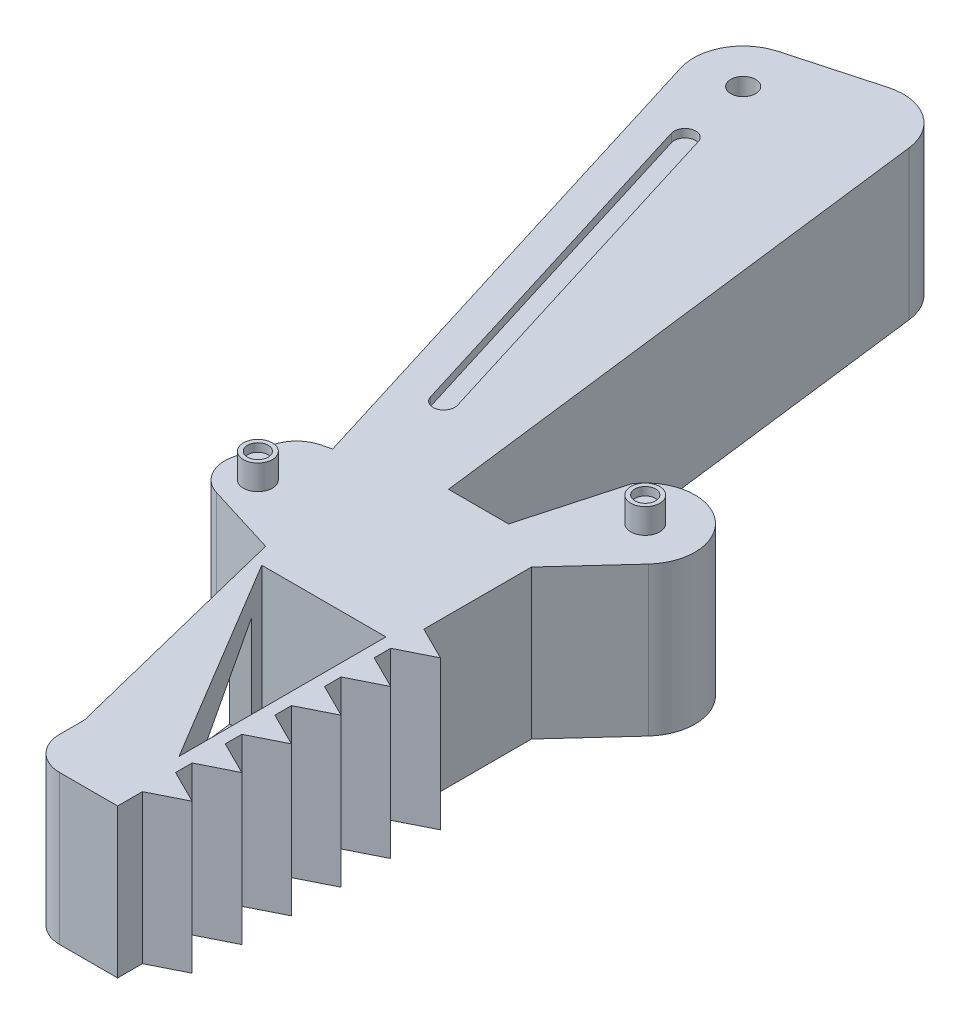
SolidWorks part; units mm, degrees
ref_plane "Plan de face" through (0, 0, 0) normal (0, 0, 1) x (1, 0, 0)
ref_plane "Plan de dessus" through (0, 0, 0) normal (0, 1, 0) x (1, 0, 0)
ref_plane "Plan de droite" through (0, 0, 0) normal (1, 0, 0) x (0, 0, -1)
sketch "Esquisse1" plane through (0, 0, 0) normal (0, 1, 0) x (1, 0, 0)
  line L0 (0, 0) -> (-69.0933, 0) construction
  line L1 (-15.9314, 0) -> (-39.0702, -6.3713)
  line L2 (-39.0702, -6.3713) -> (-18.3784, -73.2431)
  line L3 (-15.9314, 0) -> (-7.1627, -70.4564)
  line L4 (-7.1627, -70.4564) -> (-21.7201, -74.0734)
  line L5 (-21.7201, -74.0734) -> (-24.6742, -83.6271)
  line L6 (-24.6742, -83.6271) -> (-12.2544, -87.4675)
  line L7 (-12.2544, -87.4675) -> (-5.0204, -116.5822)
  line L8 (-5.0204, -116.5822) -> (-5.0204, -123.5822)
  line L9 (-5.0204, -123.5822) -> (5.9796, -123.5822)
  line L10 (5.9796, -123.5822) -> (5.9796, -73.5822)
  line L11 (5.9796, -73.5822) -> (12.7296, -66.2041)
  line L12 (-7.1627, -70.4564) -> (0.0908, -70.4564)
  line L13 (0.0908, -70.4564) -> (3.3228, -58.8074)
  arc A0 (3.3228, -58.8074) -> (12.7296, -66.2041) centre (8.3027, -62.1541) cw
  dimension "D12" = 6
  dimension "D1" = 24
  dimension "D2" = 70
  dimension "D3" = 71
  dimension "D4" = 15
  dimension "D5" = 10
  dimension "D6" = 13
  dimension "D7" = 30
  dimension "D8" = 7
  dimension "D9" = 11
  dimension "D10" = 50
  dimension "D11" = 10
extrude "Boss.-Extru.1" add sketch "Esquisse1" along normal mid plane 18
fillet "Congé1" radius 6 2 edges at (-15.9314, 0, 0) (-39.0702, 0, 6.3713)
fillet "Congé2" radius 4 3 edges at (-5.0204, 0, 123.5822) (-24.6742, 0, 83.6271) (-21.7201, 0, 74.0734)
sketch "Esquisse2" plane through (0, 9, 0) normal (0, 1, 0) x (1, 0, 0)
  line L0 (5.9796, -123.5822) -> (5.9796, -118.5822)
  line L1 (5.9796, -123.5822) -> (5.9796, -73.5822) construction
  line L2 (5.9796, -118.5822) -> (9.9796, -118.5822) construction
  line L3 (5.9796, -116.5822) -> (5.9796, -120.5822)
  line L4 (5.9796, -116.5822) -> (9.9796, -118.5822)
  line L5 (9.9796, -118.5822) -> (5.9796, -120.5822)
  point P9 (5.9796, -118.5822)
  line M7 (5.9796, -123.5822) -> (5.9796, -73.5822)
  dimension "D1" = 5
  dimension "D2" = 4
  dimension "D3" = 4
extrude "Boss.-Extru.2" add sketch "Esquisse2" against normal through all contours L2 L4 M7 | L2 L0 L5
pattern_linear "Répétition linéaire1" count 6 spacing 6 along (0, 0, -1) of "Boss.-Extru.2"
sketch "Esquisse3" plane through (0, 9, 0) normal (0, 1, 0) x (1, 0, 0)
  line L0 (4.5005, -114.6826) -> (4.5005, -89.6826)
  line L1 (4.5005, -89.6826) -> (-10.4995, -89.6826)
  line L2 (-10.4995, -89.6826) -> (4.5005, -114.6826)
  dimension "D1" = 15
  dimension "D2" = 25
extrude "Enlèv. mat.-Extru.1" cut sketch "Esquisse3" against normal through all
sketch "Esquisse4" plane through (-32.0108, 0, 7.9536) normal (-0.9705, 0, 0.2411) x (0.2411, 0, 0.9705)
  line L0 (87.9316, 6) -> (87.9316, -6)
  line L1 (87.9316, -6) -> (105.9316, -3.5)
  line L2 (105.9316, -3.5) -> (105.9316, 3.5)
  line L3 (105.9316, 3.5) -> (87.9316, 6)
  line L4 (81.9316, 9) -> (81.9316, -9) construction
  line L6 (111.9316, 9) -> (111.9316, -9) construction
  line L7 (81.9316, 9) -> (111.9316, 9) construction
  point P4 (87.9316, 0)
  point P5 (105.9316, 0)
  point P8 (81.9316, 0)
  dimension "D1" = 3
  dimension "D2" = 6
  dimension "D3" = 6
extrude "Enlèv. mat.-Extru.2" cut sketch "Esquisse4" against normal blind 10
sketch "Esquisse5" plane through (0, 9, 0) normal (0, 1, 0) x (1, 0, 0)
  circle A0 centre (-31.5082, -10.5124) radius 1.5
  dimension "D1" = 3
extrude "Enlèv. mat.-Extru.3" cut sketch "Esquisse5" against normal through all
sketch "Esquisse7" plane through (0, 9, 0) normal (0, 1, 0) x (1, 0, 0)
  circle A0 centre (-19.6711, -80.9873) radius 1.75
  circle A1 centre (8.3027, -62.1541) radius 1.75
  dimension "D1" = 3.5
  dimension "D2" = 3.5
extrude "Boss.-Extru.3" add sketch "Esquisse7" along normal blind 3
sketch "Esquisse8" plane through (0, 12, 0) normal (0, 1, 0) x (1, 0, 0)
  circle A2 centre (-19.6711, -80.9873) radius 1.25
  circle A3 centre (-19.6711, -80.9873) radius 1.25
  dimension "D1" = 0.5
extrude "Enlèv. mat.-Extru.4" cut sketch "Esquisse8" against normal blind 1
sketch "Esquisse9" plane through (0, 12, 0) normal (0, 1, 0) x (1, 0, 0)
  circle A2 centre (8.3027, -62.1541) radius 1.25
  circle A3 centre (8.3027, -62.1541) radius 1.25
  dimension "D1" = 0.5
extrude "Enlèv. mat.-Extru.5" cut sketch "Esquisse9" against normal blind 1
sketch "Esquisse10" plane through (0, 9, 0) normal (0, 1, 0) x (1, 0, 0)
  line L0 (-29.7189, -19.3379) -> (-16.6676, -61.5169) construction
  line L1 (-28.4702, -18.9515) -> (-15.4189, -61.1305)
  line L2 (-30.9675, -19.7242) -> (-17.9163, -61.9032)
  line L4 (-37.2401, -12.286) -> (-18.3784, -73.2431) construction
  arc A0 (-28.4702, -18.9515) -> (-30.9675, -19.7242) centre (-29.7189, -19.3379) ccw
  arc A1 (-17.9163, -61.9032) -> (-15.4189, -61.1305) centre (-16.6676, -61.5169) ccw
  point P2 (-23.1932, -40.4274)
  point P7 (-29.7189, -19.3379)
extrude "Enlèv. mat.-Extru.6" cut sketch "Esquisse10" against normal blind 1
mirror "Symétrie1" about plane through (0, 0, 0) normal (0, 1, 0) of "Boss.-Extru.3", "Enlèv. mat.-Extru.4", "Enlèv. mat.-Extru.5", "Enlèv. mat.-Extru.6"
